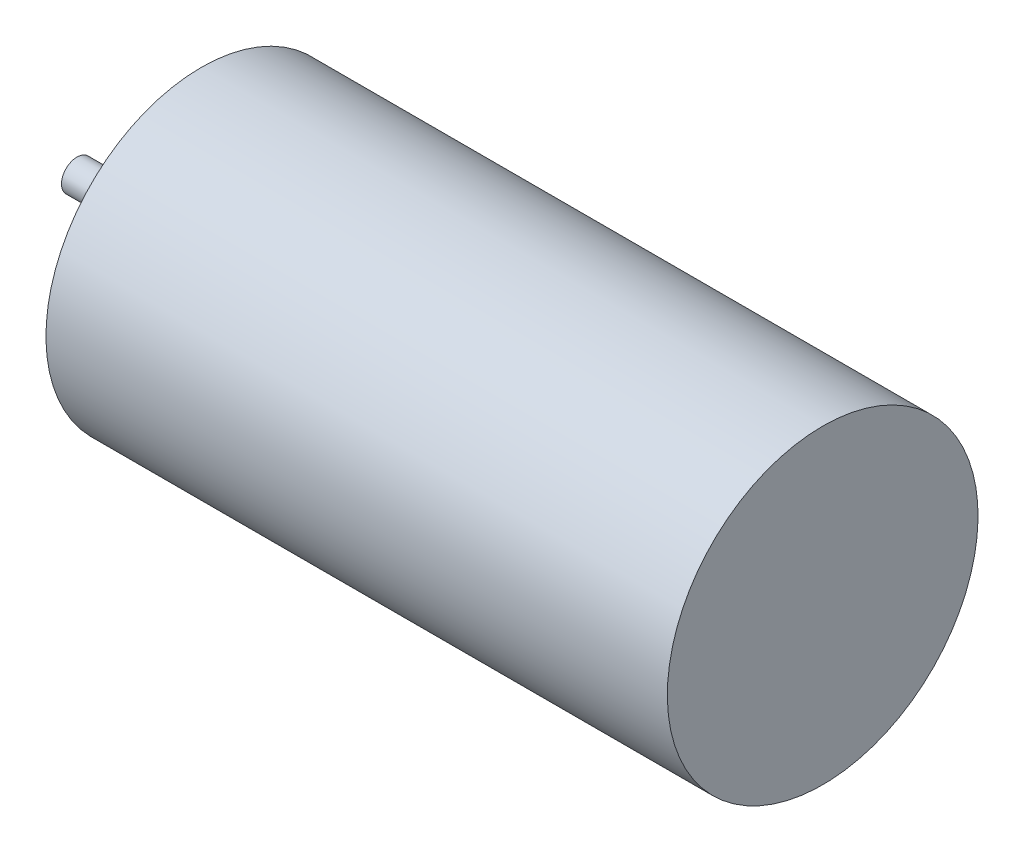
SolidWorks part; units mm, degrees
ref_plane "Front Plane" through (0, 0, 0) normal (0, 0, 1) x (1, 0, 0)
ref_plane "Top Plane" through (0, 0, 0) normal (0, 1, 0) x (1, 0, 0)
ref_plane "Right Plane" through (0, 0, 0) normal (1, 0, 0) x (0, 0, -1)
sketch "Sketch1" plane through (0, 0, 0) normal (0, 0, 1) x (1, 0, 0)
  line L0 (0, 1) -> (0, 10)
  line L1 (0, 10) -> (40, 10)
  line L2 (40, 10) -> (40, 0)
  line L3 (40, 0) -> (0, 0)
  line L5 (0, 1) -> (-8, 1)
  line L7 (0, 0) -> (-8, 0)
  line L8 (-8, 1) -> (-8, 0)
  dimension "D1" = 10
  dimension "D2" = 40
  dimension "D3" = 8
  dimension "D4" = 1
revolve "Revolve1" add sketch "Sketch1" angle 360 about L3
